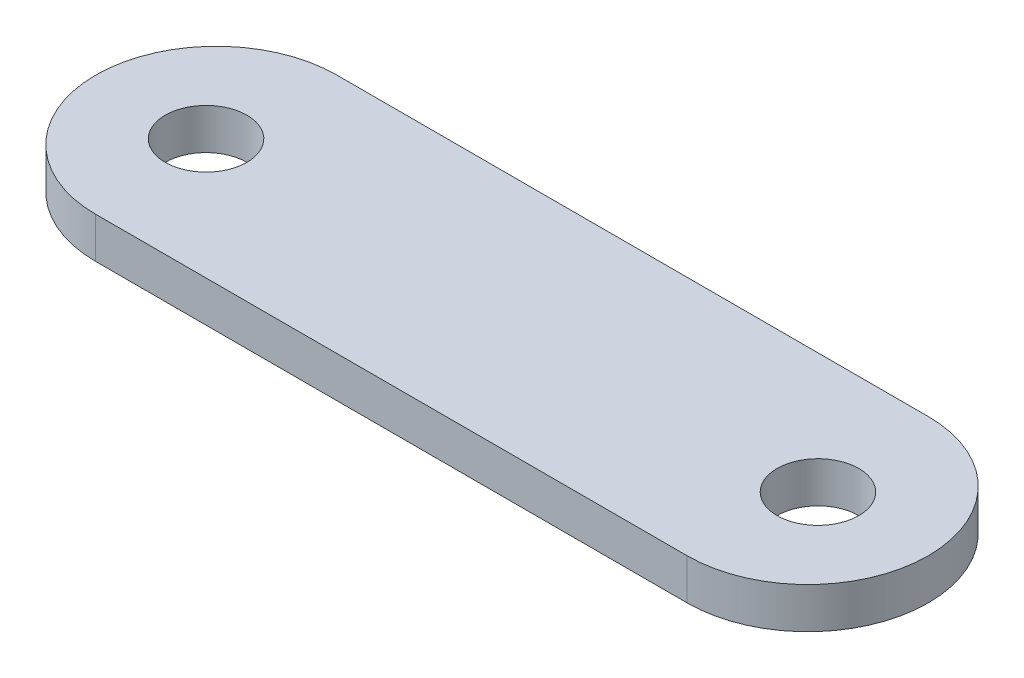
SolidWorks part; units mm, degrees
ref_plane "Front Plane" through (0, 0, 0) normal (0, 0, 1) x (1, 0, 0)
ref_plane "Top Plane" through (0, 0, 0) normal (0, 1, 0) x (1, 0, 0)
ref_plane "Right Plane" through (0, 0, 0) normal (1, 0, 0) x (0, 0, -1)
sketch "Sketch4" plane through (0, 0, 0) normal (0, 1, 0) x (1, 0, 0)
  line L0 (-69.1433, 0) -> (-40.2009, 0) construction
  line L1 (-69.1433, 5.9) -> (-40.2009, 5.9)
  line L2 (-69.1433, -5.9) -> (-40.2009, -5.9)
  line L3 (-75.0433, 0) -> (-34.3009, 0) construction
  arc A0 (-69.1433, 5.9) -> (-69.1433, -5.9) centre (-69.1433, 0) ccw
  arc A1 (-40.2009, -5.9) -> (-40.2009, 5.9) centre (-40.2009, 0) ccw
  point P2 (-54.6721, 0)
  dimension "D1" = 5.9
  dimension "D2" = 40.7424
extrude "Boss-Extrude1" add sketch "Sketch4" along normal blind 2
sketch "Sketch5" plane through (0, 0, 0) normal (0, -1, 0) x (1, 0, 0)
  line L0 (-34.3009, 0) -> (-75.0433, 0) construction
  circle A0 centre (-39.7009, 0) radius 2
  arc A1 (-40.2009, -5.9) -> (-40.2009, 5.9) centre (-40.2009, 0) ccw construction
  arc A2 (-69.1433, 5.9) -> (-69.1433, -5.9) centre (-69.1433, 0) ccw construction
  circle A3 centre (-69.6433, 0) radius 2
  point P2 (-34.3009, 0)
  dimension "D1" = 4
  dimension "D2" = 5.4
  dimension "D3" = 4
  dimension "D4" = 5.4
extrude "Cut-Extrude1" cut sketch "Sketch5" against normal through all
sketch "Sketch6" plane through (0, 0, 0) normal (0, -1, 0) x (1, 0, 0)
  line L0 (-40.2009, -5.9) -> (-69.1433, -5.9) construction
  line L1 (-67.1433, -1) -> (-65.1433, -1)
  line L2 (-67.1433, -1) -> (-67.1433, 1)
  line L3 (-67.1433, 1) -> (-65.1433, 1)
  line L4 (-65.1433, -1) -> (-65.1433, 1)
  line L5 (-67.1433, -1) -> (-65.1433, 1) construction
  line L6 (-67.1433, 1) -> (-65.1433, -1) construction
  circle A0 centre (-69.6433, 0) radius 2 construction
  point P0 (-66.1433, 0)
  dimension "D1" = 2
  dimension "D2" = 2
  dimension "D3" = 4.9
  dimension "D4" = 2.5
extrude "Boss-Extrude2" add sketch "Sketch6" along normal blind 2
